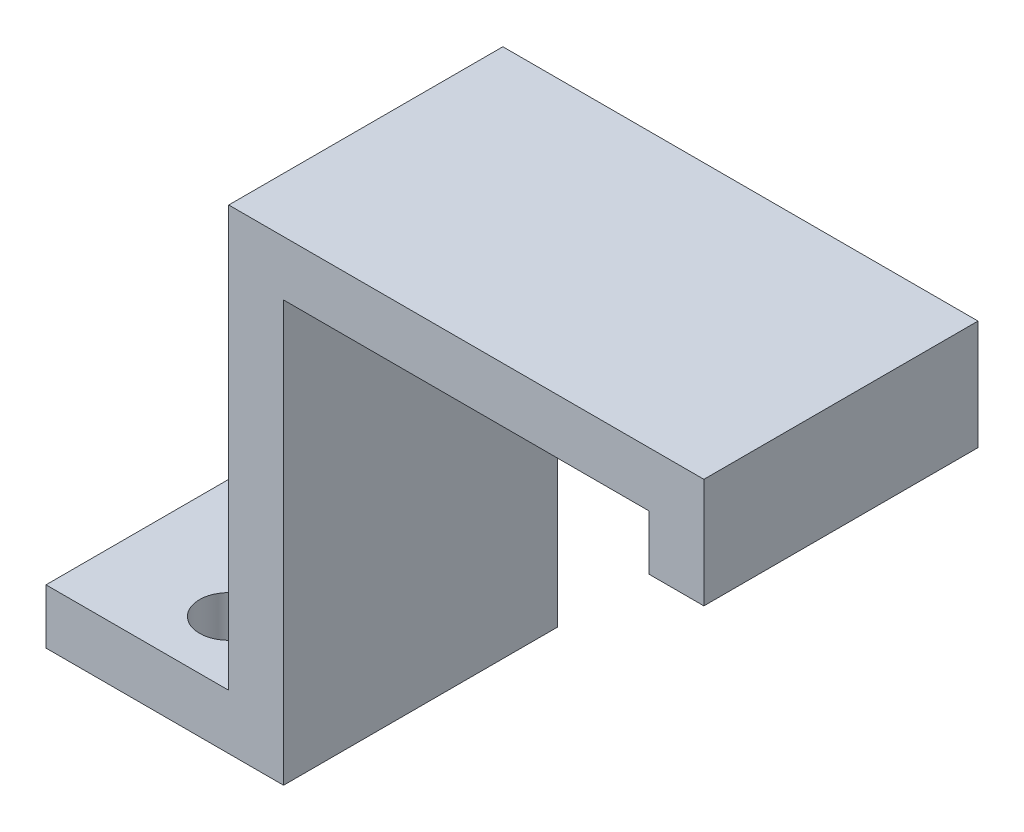
SolidWorks part; units mm, degrees
ref_plane "前基準面" through (0, 0, 0) normal (0, 0, 1) x (1, 0, 0)
ref_plane "上基準面" through (0, 0, 0) normal (0, 1, 0) x (1, 0, 0)
ref_plane "右基準面" through (0, 0, 0) normal (1, 0, 0) x (0, 0, -1)
sketch "草圖1" plane through (0, 0, 0) normal (0, 0, 1) x (1, 0, 0)
  line L0 (0, 0) -> (26, 0)
  line L1 (0, 0) -> (0, -23)
  line L2 (26, 0) -> (26, -6)
  line L3 (26, -6) -> (23, -6)
  line L4 (23, -6) -> (23, -3)
  line L5 (23, -3) -> (3, -3)
  line L6 (3, -3) -> (3, -26)
  line L7 (3, -26) -> (-10, -26)
  line L8 (-10, -26) -> (-10, -23)
  line L9 (-10, -23) -> (0, -23)
  dimension "D1" = 26
  dimension "D2" = 23
  dimension "D3" = 3
  dimension "D4" = 6
  dimension "D5" = 20
  dimension "D6" = 10
  dimension "D7" = 3
  dimension "D8" = 23
extrude "填料-伸長1" add sketch "草圖1" along normal blind 15
sketch "草圖2" plane through (0, -23, 0) normal (0, 1, 0) x (1, 0, 0)
  line L0 (0, 0) -> (-10, 0) construction
  line L1 (-10, -15) -> (-10, 0) construction
  line L2 (0, -15) -> (0, 0) construction
  line L3 (0, -15) -> (-10, -15) construction
  circle A0 centre (-6.5, -3.5) radius 1.6
  circle A1 centre (-3.5, -11.5) radius 1.6
  dimension "D1" = 3.2
  dimension "D2" = 3.2
  dimension "D3" = 3.5
  dimension "D4" = 3.5
  dimension "D5" = 3.5
  dimension "D6" = 3.5
extrude "除料-伸長1" cut sketch "草圖2" against normal blind 3 contours A0 | A1
